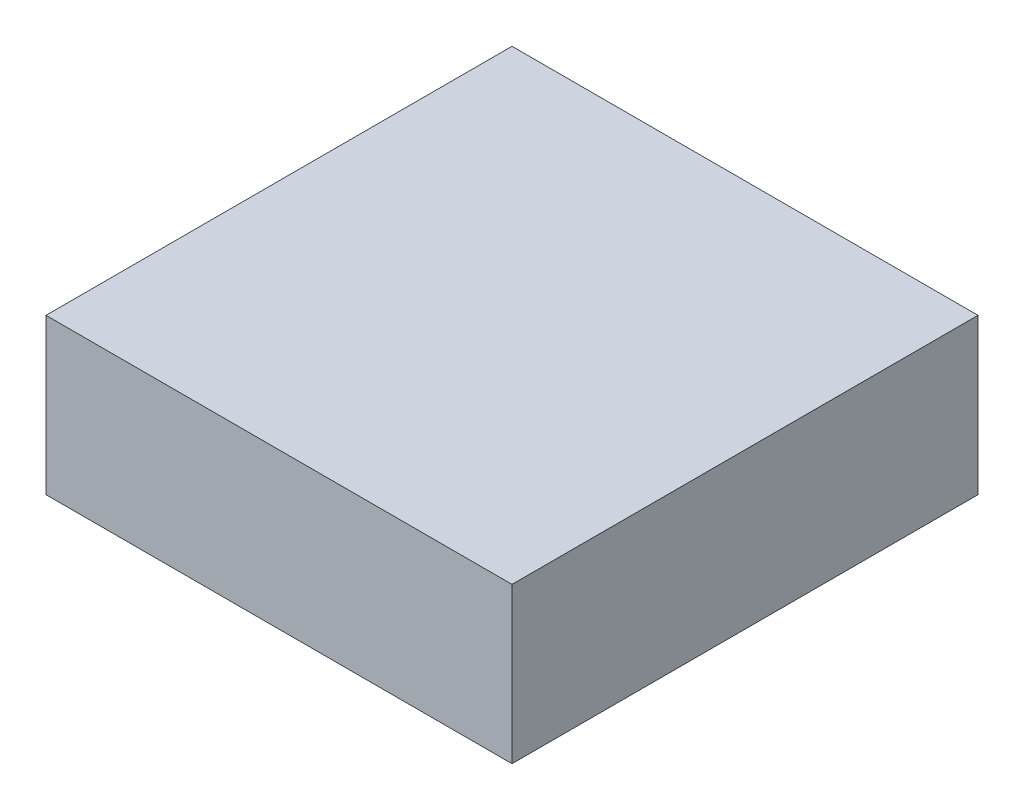
SolidWorks part; units mm, degrees
material "Pure Gold"
ref_plane "Front Plane" through (0, 0, 0) normal (0, 0, 1) x (1, 0, 0)
ref_plane "Top Plane" through (0, 0, 0) normal (0, 1, 0) x (1, 0, 0)
ref_plane "Right Plane" through (0, 0, 0) normal (1, 0, 0) x (0, 0, -1)
sketch "Sketch1" plane through (0, 0, 0) normal (1, 0, 0) x (0, 0, -1)
  line L1 (76.2, 25.4) -> (-76.2, 25.4)
  line L2 (76.2, 25.4) -> (76.2, -25.4)
  line L3 (76.2, -25.4) -> (-76.2, -25.4)
  line L4 (-76.2, 25.4) -> (-76.2, -25.4)
  line L5 (76.2, 25.4) -> (-76.2, -25.4) construction
  line L6 (76.2, -25.4) -> (-76.2, 25.4) construction
  point P0 (0, 0)
  dimension "D1" = 152.4
  dimension "D2" = 50.8
extrude "Boss-Extrude1" add sketch "Sketch1" along normal mid plane 152.4
